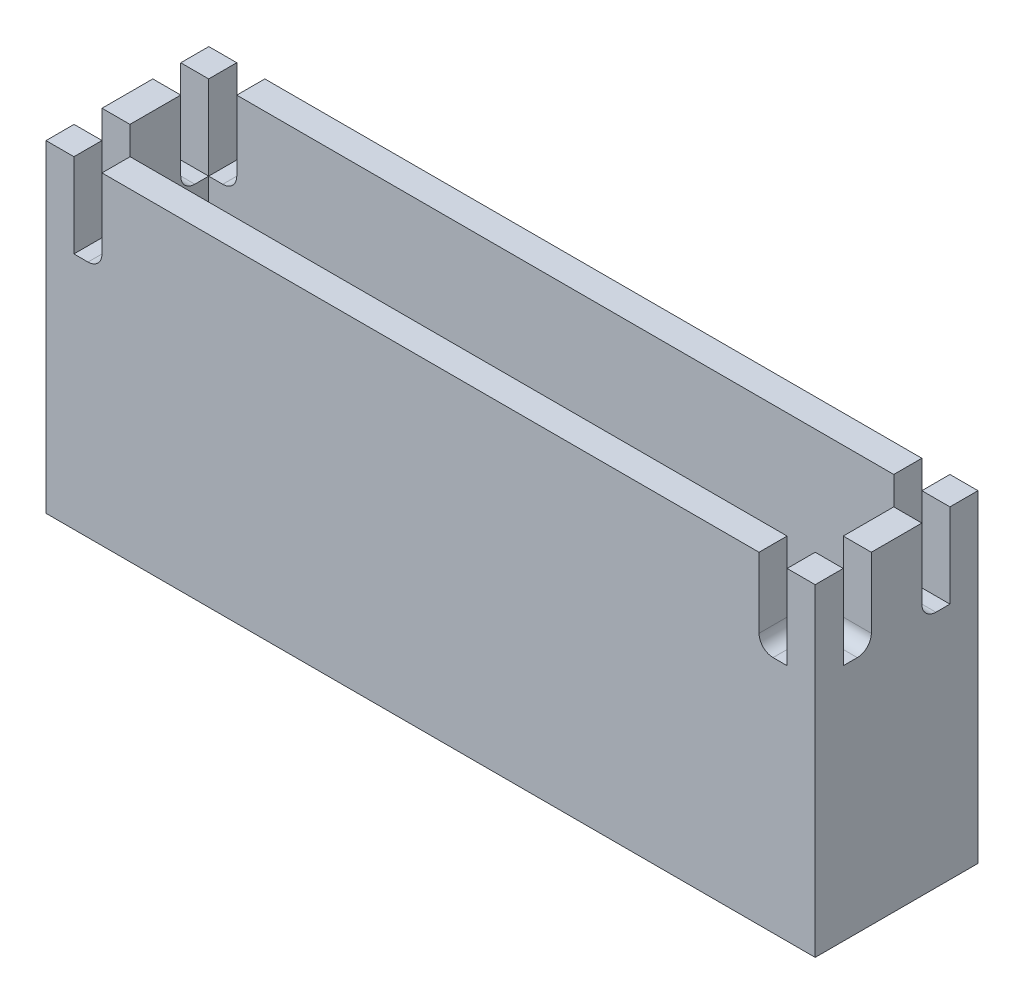
SolidWorks part; units mm, degrees
material "PP Kopolimer"
ref_plane "Front Plane" through (0, 0, 0) normal (0, 0, 1) x (1, 0, 0)
ref_plane "Top Plane" through (0, 0, 0) normal (0, 1, 0) x (1, 0, 0)
ref_plane "Right Plane" through (0, 0, 0) normal (1, 0, 0) x (0, 0, -1)
sketch "Szkic1" plane through (0, 0, 0) normal (0, 1, 0) x (1, 0, 0)
  line L1 (-12.7, -2.9) -> (12.7, -2.9)
  line L2 (-12.7, -2.9) -> (-12.7, 2.9)
  line L3 (-12.7, 2.9) -> (12.7, 2.9)
  line L4 (12.7, -2.9) -> (12.7, 2.9)
  line L5 (-12.7, -2.9) -> (12.7, 2.9) construction
  line L6 (-12.7, 2.9) -> (12.7, -2.9) construction
  point P0 (0, 0)
  dimension "D1" = 5.8
  dimension "D2" = 25.4
extrude "Dodanie-wyciągnięcie2" add sketch "Szkic1" along normal blind 3.4 contours L3 L4 L1 L2
sketch "Szkic3" plane through (0, 3.4, 0) normal (0, 1, 0) x (1, 0, 0)
  line L0 (-12.7, 0) -> (-11.75, 0) construction
  line L1 (-12.7, -2.9) -> (-12.7, 2.9) construction
  line L2 (-11.75, 0) -> (-11.11, 0) construction
  line L3 (-11.11, 0) -> (-9.21, 0) construction
  line L4 (-9.21, 0) -> (-8.57, 0) construction
  line L5 (-8.57, 0) -> (-6.67, 0) construction
  line L6 (-6.67, 0) -> (-6.03, 0) construction
  line L7 (-6.03, 0) -> (-4.13, 0) construction
  line L8 (-4.13, 0) -> (-3.49, 0) construction
  line L9 (-3.49, 0) -> (-1.59, 0) construction
  line L10 (-1.59, 0) -> (-0.95, 0) construction
  line L11 (-0.95, 0) -> (0.95, 0) construction
  line L12 (0.95, 0) -> (1.59, 0) construction
  line L13 (1.59, 0) -> (3.49, 0) construction
  line L14 (3.49, 0) -> (4.13, 0) construction
  line L15 (4.13, 0) -> (6.03, 0) construction
  line L16 (6.03, 0) -> (6.67, 0) construction
  line L17 (6.67, 0) -> (8.57, 0) construction
  line L18 (8.57, 0) -> (9.21, 0) construction
  line L19 (9.21, 0) -> (11.11, 0) construction
  line L20 (11.11, 0) -> (11.75, 0) construction
  line L21 (11.75, 0) -> (12.7, 0) construction
  line L22 (12.7, -2.9) -> (12.7, 2.9) construction
  line L24 (-11.75, -0.3218) -> (-11.11, -0.3218)
  line L25 (-11.75, -0.3218) -> (-11.75, 0.3218)
  line L26 (-11.75, 0.3218) -> (-11.11, 0.3218)
  line L27 (-11.11, -0.3218) -> (-11.11, 0.3218)
  line L28 (-11.75, -0.3218) -> (-11.11, 0.3218) construction
  line L29 (-11.75, 0.3218) -> (-11.11, -0.3218) construction
  line L30 (-9.21, -0.3218) -> (-8.57, -0.3218)
  line L31 (-9.21, -0.3218) -> (-9.21, 0.3218)
  line L32 (-9.21, 0.3218) -> (-8.57, 0.3218)
  line L33 (-8.57, -0.3218) -> (-8.57, 0.3218)
  line L34 (-9.21, -0.3218) -> (-8.57, 0.3218) construction
  line L35 (-9.21, 0.3218) -> (-8.57, -0.3218) construction
  line L36 (-6.03, -0.3218) -> (-6.67, -0.3218)
  line L37 (-6.03, -0.3218) -> (-6.03, 0.3218)
  line L38 (-6.03, 0.3218) -> (-6.67, 0.3218)
  line L39 (-6.67, -0.3218) -> (-6.67, 0.3218)
  line L40 (-6.03, -0.3218) -> (-6.67, 0.3218) construction
  line L41 (-6.03, 0.3218) -> (-6.67, -0.3218) construction
  line L42 (-3.49, -0.3218) -> (-4.13, -0.3218)
  line L43 (-3.49, -0.3218) -> (-3.49, 0.3218)
  line L44 (-3.49, 0.3218) -> (-4.13, 0.3218)
  line L45 (-4.13, -0.3218) -> (-4.13, 0.3218)
  line L46 (-3.49, -0.3218) -> (-4.13, 0.3218) construction
  line L47 (-3.49, 0.3218) -> (-4.13, -0.3218) construction
  line L48 (-0.95, -0.3218) -> (-1.59, -0.3218)
  line L49 (-0.95, -0.3218) -> (-0.95, 0.3218)
  line L50 (-0.95, 0.3218) -> (-1.59, 0.3218)
  line L51 (-1.59, -0.3218) -> (-1.59, 0.3218)
  line L52 (-0.95, -0.3218) -> (-1.59, 0.3218) construction
  line L53 (-0.95, 0.3218) -> (-1.59, -0.3218) construction
  line L54 (1.59, -0.3218) -> (0.95, -0.3218)
  line L55 (1.59, -0.3218) -> (1.59, 0.3218)
  line L56 (1.59, 0.3218) -> (0.95, 0.3218)
  line L57 (0.95, -0.3218) -> (0.95, 0.3218)
  line L58 (1.59, -0.3218) -> (0.95, 0.3218) construction
  line L59 (1.59, 0.3218) -> (0.95, -0.3218) construction
  line L60 (4.13, -0.3218) -> (3.49, -0.3218)
  line L61 (4.13, -0.3218) -> (4.13, 0.3218)
  line L62 (4.13, 0.3218) -> (3.49, 0.3218)
  line L63 (3.49, -0.3218) -> (3.49, 0.3218)
  line L64 (4.13, -0.3218) -> (3.49, 0.3218) construction
  line L65 (4.13, 0.3218) -> (3.49, -0.3218) construction
  line L66 (6.67, -0.3218) -> (6.03, -0.3218)
  line L67 (6.67, -0.3218) -> (6.67, 0.3218)
  line L68 (6.67, 0.3218) -> (6.03, 0.3218)
  line L69 (6.03, -0.3218) -> (6.03, 0.3218)
  line L70 (6.67, -0.3218) -> (6.03, 0.3218) construction
  line L71 (6.67, 0.3218) -> (6.03, -0.3218) construction
  line L72 (9.21, -0.3218) -> (8.57, -0.3218)
  line L73 (9.21, -0.3218) -> (9.21, 0.3218)
  line L74 (9.21, 0.3218) -> (8.57, 0.3218)
  line L75 (8.57, -0.3218) -> (8.57, 0.3218)
  line L76 (9.21, -0.3218) -> (8.57, 0.3218) construction
  line L77 (9.21, 0.3218) -> (8.57, -0.3218) construction
  line L78 (11.75, -0.3218) -> (11.11, -0.3218)
  line L79 (11.75, -0.3218) -> (11.75, 0.3218)
  line L80 (11.75, 0.3218) -> (11.11, 0.3218)
  line L81 (11.11, -0.3218) -> (11.11, 0.3218)
  line L82 (11.75, -0.3218) -> (11.11, 0.3218) construction
  line L83 (11.75, 0.3218) -> (11.11, -0.3218) construction
  point P27 (-11.43, 0)
  point P32 (-8.89, 0)
  point P37 (-6.35, 0)
  point P42 (-3.81, 0)
  point P47 (-1.27, 0)
  point P52 (1.27, 0)
  point P57 (3.81, 0)
  point P62 (6.35, 0)
  point P67 (8.89, 0)
  point P72 (11.43, 0)
  dimension "D1" = 0.64
  dimension "D2" = 0.6436
extrude "Wytnij-wyciągnięcie1" cut sketch "Szkic3" against normal blind 3.4
sketch "Szkic5" plane through (-12.7, 0, 0) normal (-1, 0, 0) x (0, 0, 1)
  line L1 (-2.9, 3.4) -> (2.9, 3.4)
  line L2 (-2.9, 3.4) -> (-2.9, 0)
  line L3 (-2.9, 0) -> (2.9, 0)
  line L4 (2.9, 3.4) -> (2.9, 0)
extrude "Dodanie-wyciągnięcie3" add sketch "Szkic5" along normal blind 1
sketch "Szkic6" plane through (12.7, 0, 0) normal (1, 0, 0) x (0, 0, -1)
  line L1 (2.9, 0) -> (-2.9, 0)
  line L2 (2.9, 0) -> (2.9, 3.4)
  line L3 (2.9, 3.4) -> (-2.9, 3.4)
  line L4 (-2.9, 0) -> (-2.9, 3.4)
extrude "Dodanie-wyciągnięcie4" add sketch "Szkic6" along normal blind 1
sketch "Szkic7" plane through (0, 3.4, 0) normal (0, 1, 0) x (1, 0, 0)
  line L1 (-13.7, 2.9) -> (13.7, 2.9)
  line L3 (-12.7048, 1.9) -> (12.7, 1.9)
  line L5 (13.7, 2.9) -> (13.7, -2.9)
  line L9 (-12.7048, 1.9) -> (-12.7048, -1.9)
  line L10 (-13.7, 2.9) -> (-13.7, -2.9)
  line L13 (-12.7048, -1.9) -> (12.7, -1.9)
  line L18 (12.7, -1.9) -> (12.7, 1.9)
  line L19 (-13.7, -2.9) -> (13.7, -2.9)
extrude "Dodanie-wyciągnięcie6" add sketch "Szkic7" along normal blind 8.1
sketch "Szkic8" plane through (0, 11.5, 0) normal (0, 1, 0) x (1, 0, 0)
  line L0 (-13.7, -2.9) -> (13.7, -2.9) construction
  line L1 (-12.7048, -1.9) -> (-11.7048, -1.9)
  line L2 (-12.7048, -1.9) -> (-12.7048, -2.9)
  line L3 (-12.7048, -2.9) -> (-11.7048, -2.9)
  line L4 (-11.7048, -1.9) -> (-11.7048, -2.9)
  line L5 (-13.7, 2.9) -> (-13.7, -2.9) construction
  line L6 (-12.7048, -1.9) -> (-13.7, -1.9)
  line L7 (-12.7048, -1.9) -> (-12.7048, -0.9048)
  line L8 (-12.7048, -0.9048) -> (-13.7, -0.9048)
  line L9 (-13.7, -1.9) -> (-13.7, -0.9048)
  line L10 (13.7, 2.9) -> (-13.7, 2.9) construction
  line L11 (-12.7048, 1.9) -> (-13.7, 1.9)
  line L12 (-12.7048, 1.9) -> (-12.7048, 0.9048)
  line L13 (-12.7048, 0.9048) -> (-13.7, 0.9048)
  line L14 (-13.7, 1.9) -> (-13.7, 0.9048)
  line L15 (-12.7048, 1.9) -> (-11.7048, 1.9)
  line L16 (-12.7048, 1.9) -> (-12.7048, 2.9)
  line L17 (-12.7048, 2.9) -> (-11.7048, 2.9)
  line L18 (-11.7048, 1.9) -> (-11.7048, 2.9)
  line L19 (13.7, -2.9) -> (13.7, 2.9) construction
  line L20 (12.7, -1.9) -> (11.7, -1.9)
  line L21 (12.7, -1.9) -> (12.7, -2.9)
  line L22 (12.7, -2.9) -> (11.7, -2.9)
  line L23 (11.7, -1.9) -> (11.7, -2.9)
  line L24 (12.7, -1.9) -> (13.7, -1.9)
  line L25 (12.7, -1.9) -> (12.7, -0.9)
  line L26 (12.7, -0.9) -> (13.7, -0.9)
  line L27 (13.7, -1.9) -> (13.7, -0.9)
  line L29 (12.7, 1.9) -> (13.7, 1.9)
  line L30 (12.7, 1.9) -> (12.7, 0.9)
  line L31 (12.7, 0.9) -> (13.7, 0.9)
  line L32 (13.7, 1.9) -> (13.7, 0.9)
  line L33 (12.7, 1.9) -> (11.7, 1.9)
  line L34 (12.7, 1.9) -> (12.7, 2.9)
  line L35 (12.7, 2.9) -> (11.7, 2.9)
  line L36 (11.7, 1.9) -> (11.7, 2.9)
  line M2 (-13.7, -2.9) -> (13.7, -2.9)
  line M3 (13.7, -2.9) -> (13.7, 2.9)
  line M4 (13.7, 2.9) -> (-13.7, 2.9)
  line M5 (12.7, -1.9) -> (-12.7048, -1.9)
  line M7 (-12.7048, 1.9) -> (12.7, 1.9)
  line M8 (12.7, 1.9) -> (12.7, -1.9)
extrude "Wytnij-wyciągnięcie3" cut sketch "Szkic8" against normal blind 3 contours L36 L34 M7 M4 | L31 L29 M8 M3 | L26 L24 M8 M3 | L23 L21 M5 M2 | L1 L4 L3 L2 | L6 L9 L8 L7 | L12 L13 L14 L11 | L16 L17 L18 L15
fillet "Zaokrąglenie1" radius 0.5 8 edges at (-11.7048, 8.5, 2.4) (11.7, 8.5, -2.4) (13.2, 8.5, -0.9) (13.2, 8.5, 0.9) (11.7, 8.5, 2.4) (-11.7048, 8.5, -2.4) (-13.2024, 8.5, -0.9048) (-13.2024, 8.5, 0.9048)
